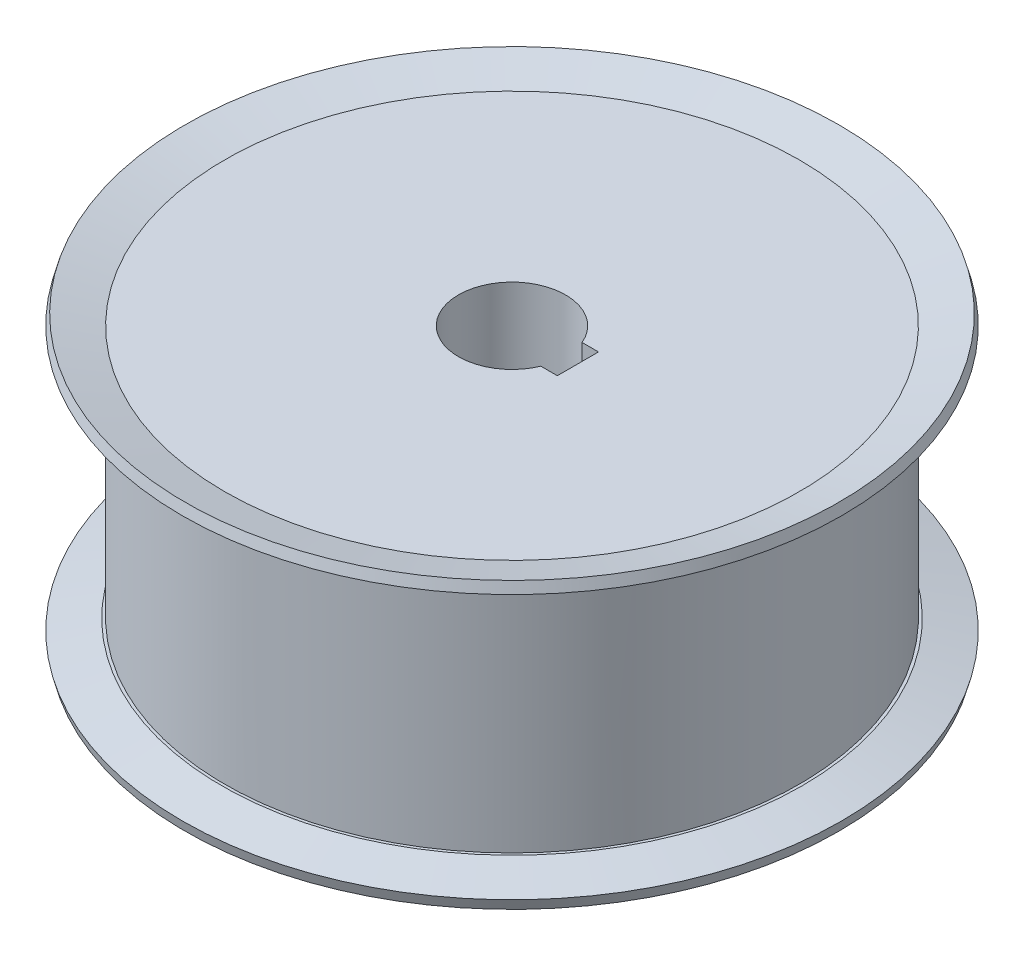
SolidWorks part; units mm, degrees
ref_plane "前视基准面" through (0, 0, 0) normal (0, 0, 1) x (1, 0, 0)
ref_plane "上视基准面" through (0, 0, 0) normal (0, 1, 0) x (1, 0, 0)
ref_plane "右视基准面" through (0, 0, 0) normal (1, 0, 0) x (0, 0, -1)
other "Configuration Table"
sketch "草图1" plane through (0, 0, 0) normal (0, 1, 0) x (1, 0, 0)
  circle A0 centre (0, 0) radius 13.95
  dimension "D1" = 27.9
extrude "凸台-拉伸1" add sketch "草图1" along normal blind 12.8
sketch "草图2" plane through (0, 12.8, 0) normal (0, 1, 0) x (1, 0, 0)
  line L0 (2.4, 1) -> (3.2, 1)
  line L1 (0, 0) -> (50000, 0) construction
  line L2 (3.2, 1) -> (3.2, -1)
  line L3 (2.4, -1) -> (3.2, -1)
  arc A0 (2.4, 1) -> (2.4, -1) centre (0, 0) ccw
  point P9 (3.2, 0)
  dimension "D1" = 5.2
  dimension "D2" = 1
  dimension "D3" = 0.8
extrude "切除-拉伸1" cut sketch "草图2" against normal blind 20
sketch "草图6" plane through (0, 0, 0) normal (0, 0, 1) x (1, 0, 0)
  line L0 (12.1412, 12.3) -> (12.1412, 12.8)
  line L1 (14.084, 12.3) -> (12.1412, 12.3)
  line L2 (15.871, 13.3147) -> (16.005, 12.8147)
  line L3 (13.95, 12.8) -> (15.871, 13.3147)
  line L4 (12.1412, 12.8) -> (13.95, 12.8)
  line L5 (14.084, 12.3) -> (16.005, 12.8147)
  line L8 (0, 0) -> (0, 50000) construction
revolve "旋转1" add sketch "草图6" angle 360 about L8
sketch "草图8" plane through (0, 0, 0) normal (0, 0, 1) x (1, 0, 0)
  line L0 (12.1412, 0.5) -> (12.1412, 0)
  line L1 (14.084, 0.5) -> (12.1412, 0.5)
  line L2 (15.871, -0.5147) -> (16.005, -0.0147)
  line L3 (13.95, 0) -> (15.871, -0.5147)
  line L4 (12.1412, 0) -> (13.95, 0)
  line L5 (14.084, 0.5) -> (16.005, -0.0147)
  line L8 (0, 0) -> (0, 50000) construction
revolve "旋转2" add sketch "草图8" angle 360 about L8
